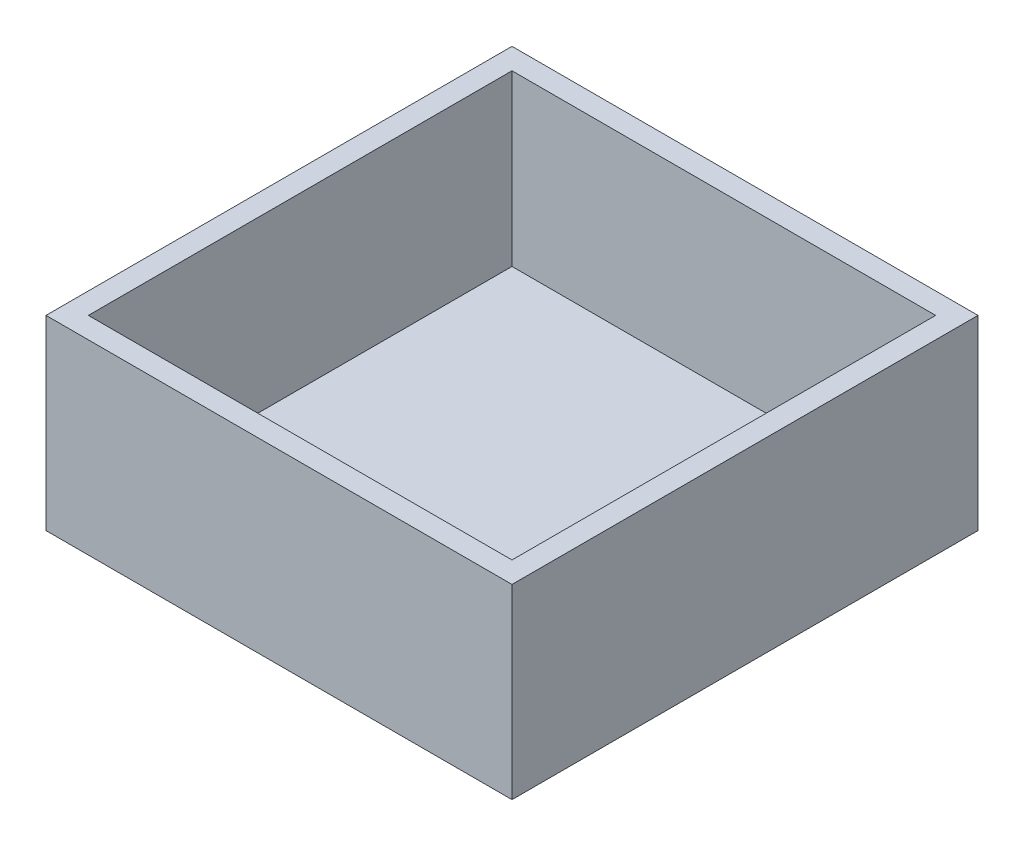
SolidWorks part; units mm, degrees
ref_plane "前视基准面" through (0, 0, 0) normal (0, 0, 1) x (1, 0, 0)
ref_plane "上视基准面" through (0, 0, 0) normal (0, 1, 0) x (1, 0, 0)
ref_plane "右视基准面" through (0, 0, 0) normal (1, 0, 0) x (0, 0, -1)
sketch "草图1" plane through (0, 0, 0) normal (0, 1, 0) x (1, 0, 0)
  line L0 (0, 0) -> (100, 0)
  line L1 (0, 0) -> (0, -100)
  line L2 (100, 0) -> (100, -100)
  line L3 (0, -100) -> (100, -100)
  line L4 (-5, 5) -> (-5, -105)
  line L5 (-5, -105) -> (105, -105)
  line L6 (105, 5) -> (105, -105)
  line L7 (-5, 5) -> (105, 5)
  dimension "D1" = 5
  dimension "D2" = 110
  dimension "D3" = 100
  dimension "D4" = 100
extrude "凸台-拉伸1" add sketch "草图1" along normal blind 40
sketch "草图2" plane through (0, 0, 0) normal (0, -1, 0) x (1, 0, 0)
  line L0 (-5, 105) -> (105, 105)
  line L1 (105, 105) -> (105, -5)
  line L2 (105, -5) -> (-5, -5)
  line L3 (-5, -5) -> (-5, 105)
extrude "凸台-拉伸2" add sketch "草图2" along normal blind 4
